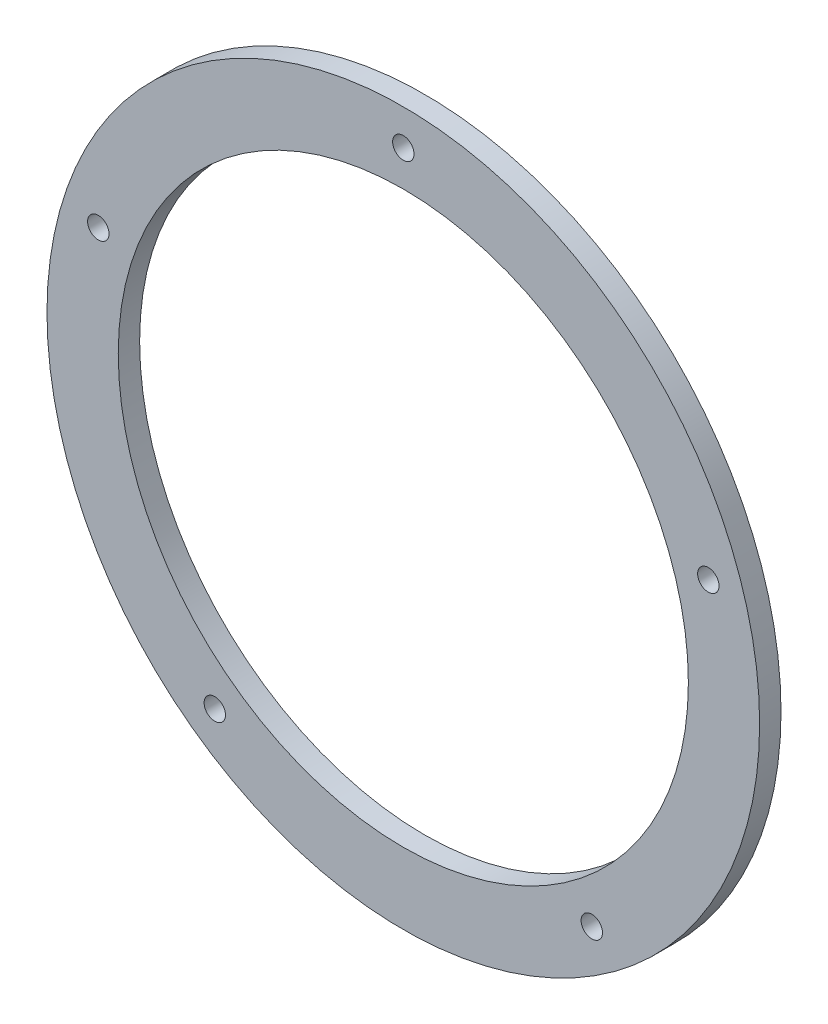
SolidWorks part; units mm, degrees
material "ABS"
ref_plane "前基準面" through (0, 0, 0) normal (0, 0, 1) x (1, 0, 0)
ref_plane "上基準面" through (0, 0, 0) normal (0, 1, 0) x (1, 0, 0)
ref_plane "右基準面" through (0, 0, 0) normal (1, 0, 0) x (0, 0, -1)
sketch "草圖1" plane through (0, 0, 0) normal (0, 0, 1) x (1, 0, 0)
  circle A0 centre (0, 0) radius 40
  circle A1 centre (0, 0) radius 50
  dimension "D1" = 80
  dimension "D2" = 100
extrude "填料-伸長1" add sketch "草圖1" along normal blind 3
sketch "草圖2" plane through (0, 0, 3) normal (0, 0, 1) x (1, 0, 0)
  line L0 (0, 45) -> (0, 0) construction
  circle A0 centre (0, 45) radius 1.5
  dimension "D2" = 3
  dimension "D1" = 45
extrude "除料-伸長1" cut sketch "草圖2" against normal through all
pattern_circular "環狀複製排列1" count 5 over 360 about axis through (0, 0, 0) along (0, 0, 1) of "除料-伸長1"
